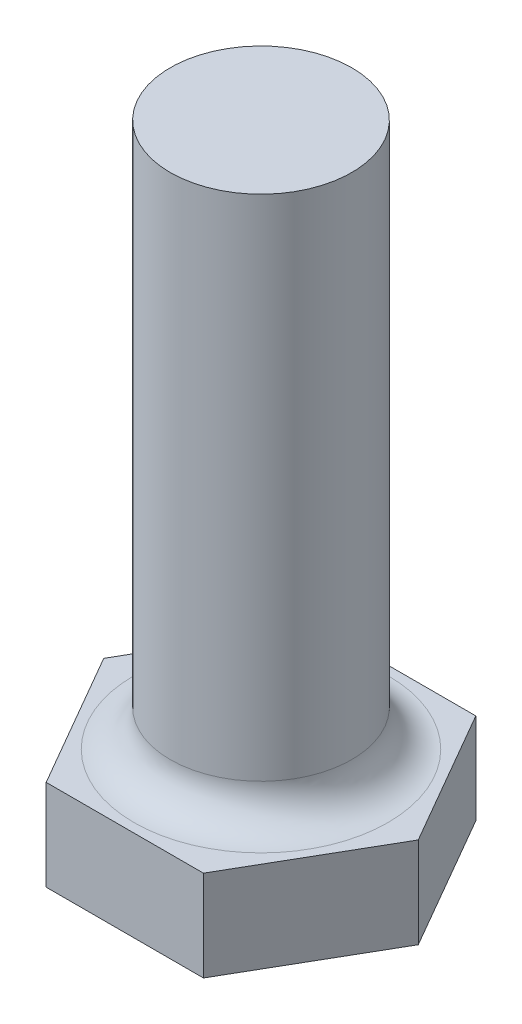
SolidWorks part; units mm, degrees
ref_plane "Front Plane" through (0, 0, 0) normal (0, 0, 1) x (1, 0, 0)
ref_plane "Top Plane" through (0, 0, 0) normal (0, 1, 0) x (1, 0, 0)
ref_plane "Right Plane" through (0, 0, 0) normal (1, 0, 0) x (0, 0, -1)
sketch "Sketch1" plane through (0, 0, 0) normal (0, 1, 0) x (1, 0, 0)
  line L1 (8.6603, 0) -> (4.3301, 7.5)
  line L2 (4.3301, 7.5) -> (-4.3301, 7.5)
  line L3 (-4.3301, 7.5) -> (-8.6603, 0)
  line L4 (-8.6603, 0) -> (-4.3301, -7.5)
  line L5 (-4.3301, -7.5) -> (4.3301, -7.5)
  line L6 (4.3301, -7.5) -> (8.6603, 0)
  circle A0 centre (0, 0) radius 7.5 construction
extrude "Boss-Extrude1" add sketch "Sketch1" along normal blind 5
sketch "Sketch2" plane through (0, 5, 0) normal (0, 1, 0) x (1, 0, 0)
  circle A0 centre (0, 0) radius 5
extrude "Boss-Extrude2" add sketch "Sketch2" along normal blind 30
fillet "Fillet1" radius 2 1 edges at (0, 5, 5)
